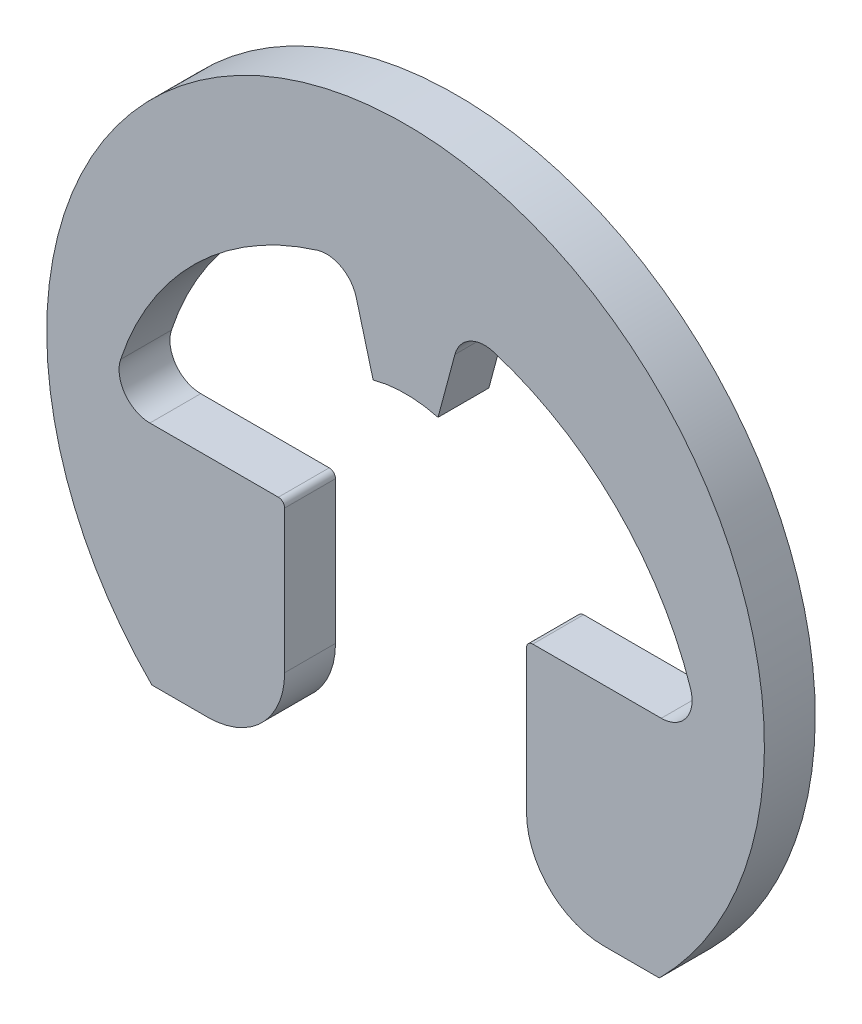
SolidWorks part; units mm, degrees
ref_plane "Plane1" through (0, 0, 0) normal (0, 0, 1) x (1, 0, 0)
ref_plane "Plane2" through (0, 0, 0) normal (0, 1, 0) x (1, 0, 0)
ref_plane "Plane3" through (0, 0, 0) normal (1, 0, 0) x (0, 0, -1)
sketch "Clipboard" plane through (0, 0, 0) normal (0, 0, 1) x (1, 0, 0)
  line L0 (0, 0) -> (1.0494, 0)
  circle A0 centre (0, 0) radius 0.9144
  circle A1 centre (0, 0) radius 2.6162
  dimension "FreeID" = 1.8288
  dimension "FreeOD" = 5.2324
  dimension "LargeSection" = 1.0494
sketch "BodySke" plane through (0, 0, 0) normal (0, 0, 1) x (1, 0, 0)
  line L0 (-2.1642, 0) -> (2.1642, 0) construction
  line L1 (0, 0) -> (0, 1.6394) construction
  line L2 (0, 0) -> (0.1962, 0.7323) construction
  line L3 (0, 0) -> (2.5973, -0.6959) construction
  line L4 (0, 0) -> (-0.1962, 0.7323) construction
  line L5 (0, 0) -> (-2.5973, -0.6959) construction
  line L6 (0, 0) -> (1.9013, -1.9013) construction
  line L7 (0, 0) -> (-1.9013, -1.9013) construction
  line L8 (1.9013, -1.9013) -> (1.4834, -1.9013)
  line L9 (-1.4834, -1.9013) -> (-1.9013, -1.9013)
  line L10 (0.9532, -0.2084) -> (1.916, -0.2084)
  line L11 (0.3696, 1.3793) -> (0.2432, 0.9078)
  line L12 (-0.3696, 1.3793) -> (-0.2432, 0.9078)
  line L13 (0.9062, -0.2554) -> (0.9062, -1.3241)
  line L14 (-0.9532, -0.2084) -> (-1.916, -0.2084)
  line L15 (-0.9062, -0.2554) -> (-0.9062, -1.3241)
  circle A0 centre (0, 0) radius 0.9398 construction
  arc A1 (2.1642, 0) -> (-2.1642, 0) centre (0, -0.6087) ccw construction
  arc A2 (1.9013, -1.9013) -> (-1.9013, -1.9013) centre (0, 0) ccw
  arc A3 (0.9532, -0.2084) -> (0.9062, -0.2554) centre (0.9532, -0.2554) ccw
  arc A4 (-0.9062, -0.2554) -> (-0.9532, -0.2084) centre (-0.9532, -0.2554) ccw
  arc A5 (-2.1352, 0.0947) -> (-0.6604, 1.5402) centre (0, -0.6087) cw
  arc A6 (-0.2432, 0.9078) -> (0.2432, 0.9078) centre (0, 0) cw
  arc A7 (0.6604, 1.5402) -> (2.1352, 0.0947) centre (0, -0.6087) cw
  arc A8 (1.916, -0.2084) -> (2.1352, 0.0947) centre (1.916, 0.0225) ccw
  arc A9 (0.6604, 1.5402) -> (0.3696, 1.3793) centre (0.5926, 1.3195) ccw
  arc A10 (-0.3696, 1.3793) -> (-0.6604, 1.5402) centre (-0.5926, 1.3195) ccw
  arc A11 (-2.1352, 0.0947) -> (-1.916, -0.2084) centre (-1.916, 0.0225) ccw
  arc A12 (0.9062, -1.3241) -> (1.4834, -1.9013) centre (1.4834, -1.3241) ccw
  arc A13 (-1.4834, -1.9013) -> (-0.9062, -1.3241) centre (-1.4834, -1.3241) ccw
  dimension "GrooveDia" = 1.8796
  dimension "OutsideDia" = 5.3777
  dimension "InnerTipRad" = 0.047
  dimension "CavityFilletRad" = 0.2309
  dimension "OuterTipRadius" = 0.5772
  dimension "D3" = 30
  dimension "D1" = 15
  dimension "CavityWidth" = 4.3283
  dimension "CavityHeight" = 1.6394
extrude "Body" add sketch "BodySke" against normal blind 0.381
equation "' \"FreeID@Clipboard\" = 0.072"
equation "' \"Thickness@Body\" = 0.015"
equation "' \"GrooveDia@BodySke\" = 0.074"
equation "' \"FreeOD@Clipboard\" = 0.206"
equation "' \"FreeID@Clipboard\" = 0.430"
equation "' \"Thickness@Body\" = 0.042"
equation "' \"GrooveDia@BodySke\" = 0.437"
equation "' \"FreeOD@Clipboard\" = 0.870"
equation "\"OutsideDia@BodySke\" = ( \"GrooveDia@BodySke\"  /  \"FreeID@Clipboard\" )  * \"FreeOD@Clipboard\""
equation "\"LargeSection@Clipboard\" =  (\"OutsideDia@BodySke\" - \"GrooveDia@BodySke\") / 2 * 0.6"
equation "\"CavityHeight@BodySke\" = \"OutsideDia@BodySke\"  /  2 - \"LargeSection@Clipboard\""
equation "\"CavityWidth@BodySke\" = \"OutsideDia@BodySke\" -  \"LargeSection@Clipboard\""
equation "\"CavityFilletRad@BodySke\" =  (\"CavityHeight@BodySke\" * 2 - \"GrooveDia@BodySke\") / 2 * 0.33"
equation "\"InnerTipRad@BodySke\" = \"GrooveDia@BodySke\" * 0.025"
equation "\"OuterTipRadius@BodySke\" =  (\"OutsideDia@BodySke\" - \"GrooveDia@BodySke\") / 2 * 0.33"
